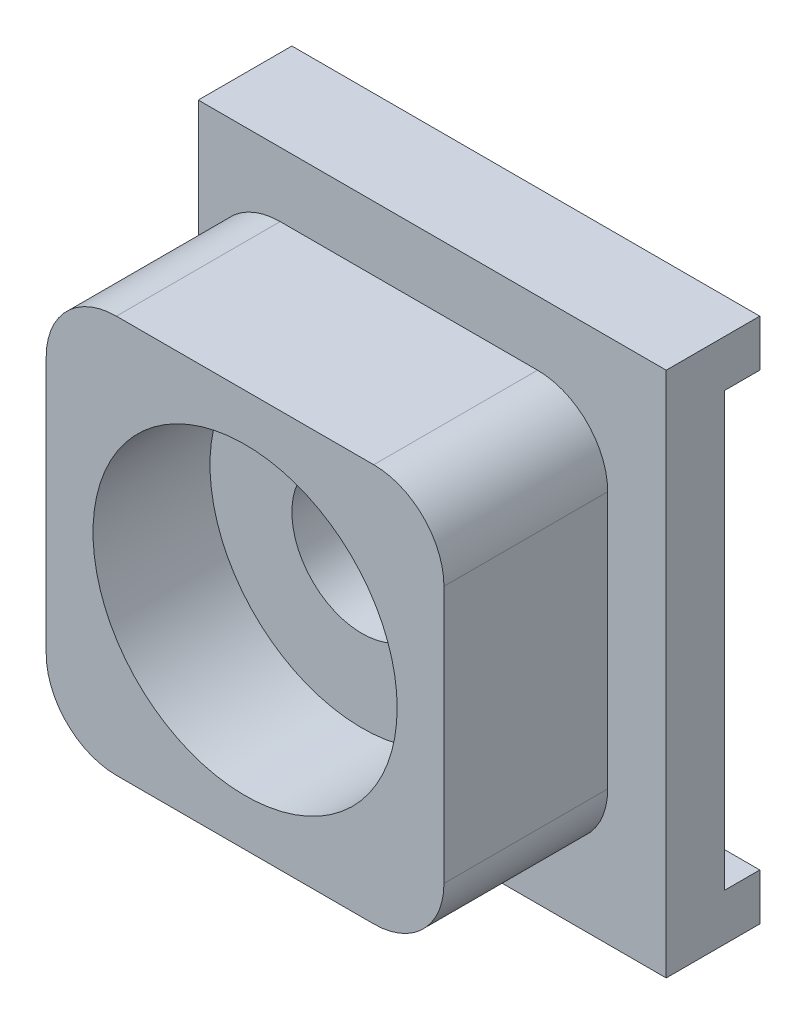
SolidWorks part; units mm, degrees
ref_plane "Front Plane" through (0, 0, 0) normal (0, 0, 1) x (1, 0, 0)
ref_plane "Top Plane" through (0, 0, 0) normal (0, 1, 0) x (1, 0, 0)
ref_plane "Right Plane" through (0, 0, 0) normal (1, 0, 0) x (0, 0, -1)
sketch "Sketch1" plane through (0, 0, 0) normal (1, 0, 0) x (0, 0, -1)
  line L0 (2.7854, -22.8661) -> (4.2854, -22.8661)
  line L1 (4.2854, -22.8661) -> (4.2854, -20.8661)
  line L2 (4.2854, -20.8661) -> (0.2854, -20.8661)
  line L3 (0.2854, -20.8661) -> (0.2854, -43.3661)
  line L4 (0.2854, -43.3661) -> (4.2854, -43.3661)
  line L5 (4.2854, -43.3661) -> (4.2854, -41.3661)
  line L6 (4.2854, -41.3661) -> (2.7854, -41.3661)
  line L7 (2.7854, -41.3661) -> (2.7854, -22.8661)
  dimension "D1" = 4
  dimension "D2" = 2.5
  dimension "D3" = 2
  dimension "D4" = 18.5
extrude "Boss-Extrude1" add sketch "Sketch1" along normal blind 20
sketch "Sketch2" plane through (0, 0, -0.2854) normal (0, 0, 1) x (1, 0, 0)
  line L0 (0, -32.1161) -> (20, -32.1161) construction
  line L1 (0, -20.8661) -> (0, -43.3661) construction
  line L2 (20, -20.8661) -> (20, -43.3661) construction
  circle A0 centre (9, -32.1161) radius 3
  dimension "D1" = 6
  dimension "D2" = 9
extrude "Cut-Extrude1" cut sketch "Sketch2" against normal blind 3
sketch "Sketch3" plane through (0, 0, -0.2854) normal (0, 0, 1) x (1, 0, 0)
  line L1 (0.5, -40.6161) -> (17.5, -40.6161)
  line L2 (0.5, -40.6161) -> (0.5, -23.6161)
  line L3 (0.5, -23.6161) -> (17.5, -23.6161)
  line L4 (17.5, -40.6161) -> (17.5, -23.6161)
  circle A0 centre (9, -32.1161) radius 3 construction
  circle A1 centre (9, -32.1161) radius 3
  dimension "D3" = 8.5
  dimension "D4" = 8.5
  dimension "D1" = 17
  dimension "D2" = 17
extrude "Boss-Extrude2" add sketch "Sketch3" along normal blind 7
sketch "Sketch4" plane through (0, 0, 6.7146) normal (0, 0, 1) x (1, 0, 0)
  circle A0 centre (9, -32.1161) radius 6.5
  dimension "D1" = 13
extrude "Cut-Extrude2" cut sketch "Sketch4" against normal blind 5
fillet "Fillet1" radius 3 4 edges at (17.5, -40.6161, 3.2146) (17.5, -23.6161, 3.2146) (0.5, -23.6161, 3.2146) (0.5, -40.6161, 3.2146)
